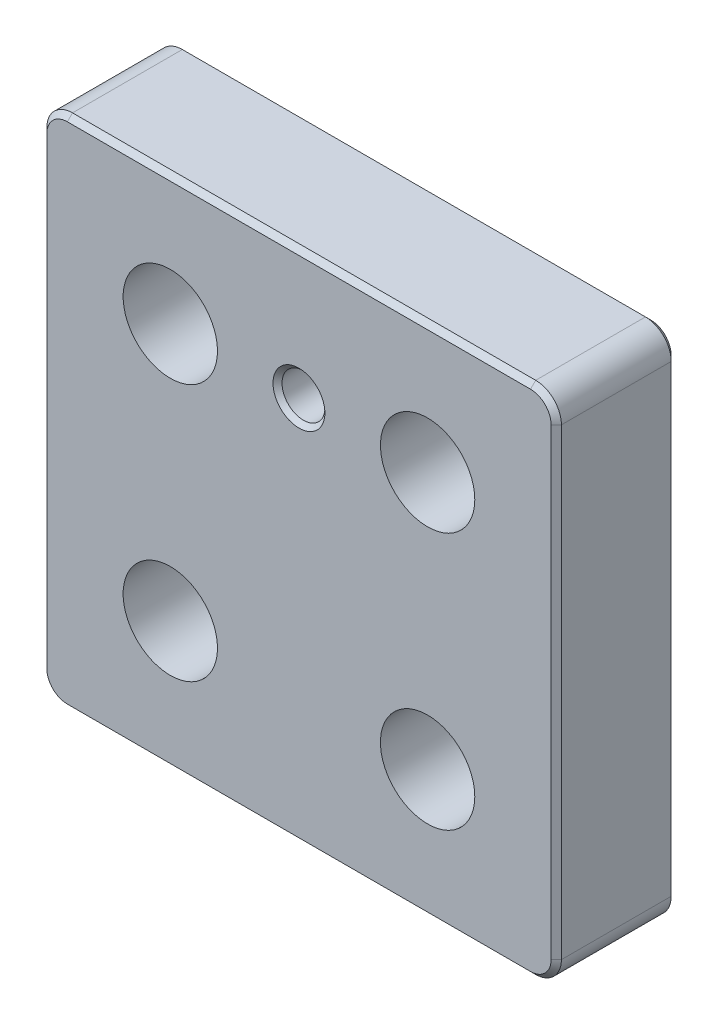
SolidWorks part; units mm, degrees
material "6061 Alloy"
ref_plane "Front Plane" through (0, 0, 0) normal (0, 0, 1) x (1, 0, 0)
ref_plane "Top Plane" through (0, 0, 0) normal (0, 1, 0) x (1, 0, 0)
ref_plane "Right Plane" through (0, 0, 0) normal (1, 0, 0) x (0, 0, -1)
sketch "Sketch1" plane through (0, 0, 0) normal (0, 0, 1) x (1, 0, 0)
  line L1 (30, -30) -> (-30, -30)
  line L2 (30, -30) -> (30, 30)
  line L3 (30, 30) -> (-30, 30)
  line L4 (-30, -30) -> (-30, 30)
  line L5 (30, -30) -> (-30, 30) construction
  line L6 (30, 30) -> (-30, -30) construction
  point P0 (0, 0)
  dimension "D1" = 60
  dimension "D2" = 60
extrude "Boss-Extrude1" add sketch "Sketch1" along normal blind 14
hole_wizard "CBORE for M6 Hex Socket Head Cap Screw1" positions "Sketch2" profile "Sketch4" counterbore size "M6" standard "DIN" end condition up to next
sketch "Sketch2" plane through (0, 0, 14) normal (0, 0, 1) x (1, 0, 0)
  line L0 (0, 0) -> (0, 30) construction
  line L1 (30, 30) -> (-30, 30) construction
  line L3 (0, 0) -> (30, 0) construction
  line L4 (30, -30) -> (30, 30) construction
  point P0 (-15, 15)
  point P2 (15, 15)
  point P4 (15, -15)
  point P20 (-15, -15)
  dimension "D1" = 30
  dimension "D2" = 30
sketch "Sketch4" plane through (-15, 15, 14) normal (1, 0, 0) x (0, -1, 0)
  line L0 (0, 0) -> (0, 14)
  line L1 (0, 14) -> (3.25, 14)
  line L3 (3.25, 14) -> (3.25, 8)
  line L4 (3.25, 8) -> (5.5, 8)
  line L5 (5.5, 8) -> (5.5, 0)
  line L7 (5.5, 0) -> (0, 0)
  line L11 (0, -6.35) -> (0, 107.95) construction
  dimension "Thru Hole Dia." = 6.5
  dimension "Thru Hole Depth" = 14
  dimension "C'Bore Dia." = 11
  dimension "C'Bore Depth" = 8
hole_wizard "M6 Tapped Hole1" positions "Sketch5" profile "Sketch7" tap size "M6" standard "DIN" end condition up to next
sketch "Sketch5" plane through (0, 0, 14) normal (0, 0, 1) x (1, 0, 0)
  line L0 (-15, 15) -> (15, 15) construction
  point P0 (0, 15)
  point P27 (0, 15)
sketch "Sketch7" plane through (0, 15, 14) normal (1, 0, 0) x (0, -1, 0)
  line L0 (0, 0) -> (0, 14)
  line L1 (0, 14) -> (2.5, 14)
  line L2 (2.5, 14) -> (2.5, 0.525)
  line L3 (2.5, 0.525) -> (3.025, 0)
  line L5 (3.025, 0) -> (0, 0)
  line L6 (-2.5, 0.525) -> (-3.025, 0) construction
  line L11 (0, -6.35) -> (0, 107.95) construction
  dimension "Thru Tap Drill Dia." = 5
  dimension "Thru Tap Drill Depth" = 14
  dimension "Near C'Sink Dia." = 6.05
  dimension "Near C'Sink Angle" = 90
cosmetic thread "Hole Thread1" parameters "D2"=6
fillet "Fillet1" radius 3 4 edges at (-30, 30, 7) (30, 30, 7) (30, -30, 7) (-30, -30, 7)
chamfer "Chamfer1" distance 0.6 angle 45 16 edges at (-29.1213, -29.1213, 0) (0, -30, 0) (29.1213, -29.1213, 0) (30, 0, 0) (29.1213, 29.1213, 0) (0, 30, 0) (-29.1213, 29.1213, 0) (-30, 0, 0) (29.1213, 29.1213, 14) (30, 0, 14) (29.1213, -29.1213, 14) (0, -30, 14) (-29.1213, -29.1213, 14) (-30, 0, 14) (-29.1213, 29.1213, 14) (0, 30, 14)
